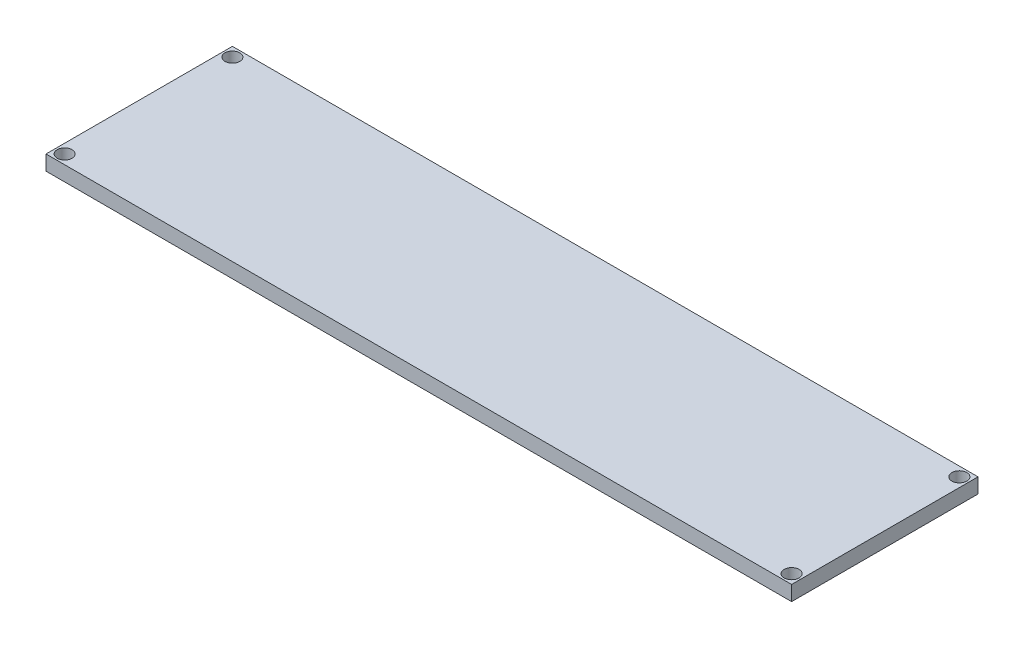
SolidWorks part; units mm, degrees
ref_plane "Płaszczyzna przednia" through (0, 0, 0) normal (0, 0, 1) x (1, 0, 0)
ref_plane "Płaszczyzna górna" through (0, 0, 0) normal (0, 1, 0) x (1, 0, 0)
ref_plane "Płaszczyzna prawa" through (0, 0, 0) normal (1, 0, 0) x (0, 0, -1)
sketch "Szkic1" plane through (0, 0, 0) normal (0, 1, 0) x (1, 0, 0)
  line L1 (0, 0) -> (80, 0)
  line L2 (0, 0) -> (0, 20)
  line L3 (0, 20) -> (80, 20)
  line L4 (80, 0) -> (80, 20)
  line L6 (0, 0) -> (0, 20)
  line L7 (80, 0) -> (80, 20)
  circle A4 centre (1, 19) radius 0.8
  circle A5 centre (1, 1) radius 0.8
  circle A6 centre (79, 1) radius 0.8
  circle A7 centre (79, 19) radius 0.8
  point P10 (14, 10)
  dimension "D1" = 20
  dimension "D3" = 1.6
  dimension "D2" = 80
extrude "Dodanie-wyciągnięcie1" add sketch "Szkic1" along normal blind 1.6
